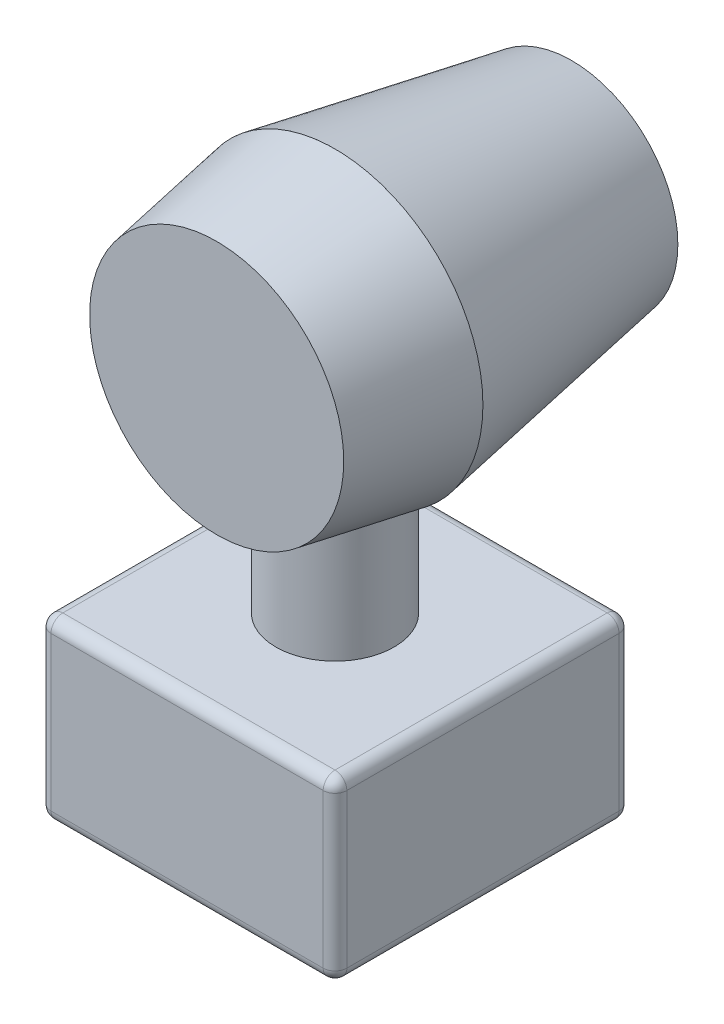
SolidWorks part; units mm, degrees
ref_plane "Front Plane" through (0, 0, 0) normal (0, 0, 1) x (1, 0, 0)
ref_plane "Top Plane" through (0, 0, 0) normal (0, 1, 0) x (1, 0, 0)
ref_plane "Right Plane" through (0, 0, 0) normal (1, 0, 0) x (0, 0, -1)
sketch "Sketch1" plane through (0, 0, 0) normal (0, 0, 1) x (1, 0, 0)
  line L1 (-31.75, -19.05) -> (31.75, -19.05)
  line L2 (-31.75, -19.05) -> (-31.75, 19.05)
  line L3 (-31.75, 19.05) -> (31.75, 19.05)
  line L4 (31.75, -19.05) -> (31.75, 19.05)
  line L5 (-31.75, -19.05) -> (31.75, 19.05) construction
  line L6 (-31.75, 19.05) -> (31.75, -19.05) construction
  point P0 (0, 0)
  dimension "D1" = 63.5
  dimension "D2" = 38.1
extrude "Boss-Extrude1" add sketch "Sketch1" along normal mid plane 63.5
fillet "Fillet1" radius 2.54 12 edges at (-31.75, 0, -31.75) (-31.75, 0, 31.75) (31.75, 0, 31.75) (31.75, 0, -31.75) (-31.75, -19.05, 0) (0, -19.05, 31.75) (31.75, -19.05, 0) (0, -19.05, -31.75) (31.75, 19.05, 0) (0, 19.05, 31.75) (-31.75, 19.05, 0) (0, 19.05, -31.75)
sketch "Sketch2" plane through (0, 19.05, 0) normal (0, 1, 0) x (-1, 0, 0)
  circle A0 centre (0, 0) radius 12.7
  dimension "D1" = 25.4
extrude "Boss-Extrude2" add sketch "Sketch2" along normal blind 25.4 separate body
sketch "Sketch3" plane through (0, 0, 0) normal (0, 0, 1) x (1, 0, 0)
  line L0 (12.7, 19.05) -> (12.7, 44.45) construction
  line L1 (-12.7, 44.45) -> (-12.7, 19.05) construction
  line L2 (12.7, 44.45) -> (-12.7, 44.45) construction
  circle A0 centre (0, 73.5494) radius 31.75
  point P2 (-12.7, 44.45)
  point P4 (12.7, 44.45)
  dimension "D1" = 63.5
extrude "Boss-Extrude3" add sketch "Sketch3" against normal blind 50.8 draft 10
sketch "Sketch4" plane through (0, 0, 0) normal (0, 0, 1) x (1, 0, 0)
  circle A0 centre (0, 73.5494) radius 31.75
  arc A1 (12.7, 44.45) -> (-12.7, 44.45) centre (0, 73.5494) ccw construction
extrude "Boss-Extrude4" add sketch "Sketch4" along normal blind 25.4 draft 10 separate body
